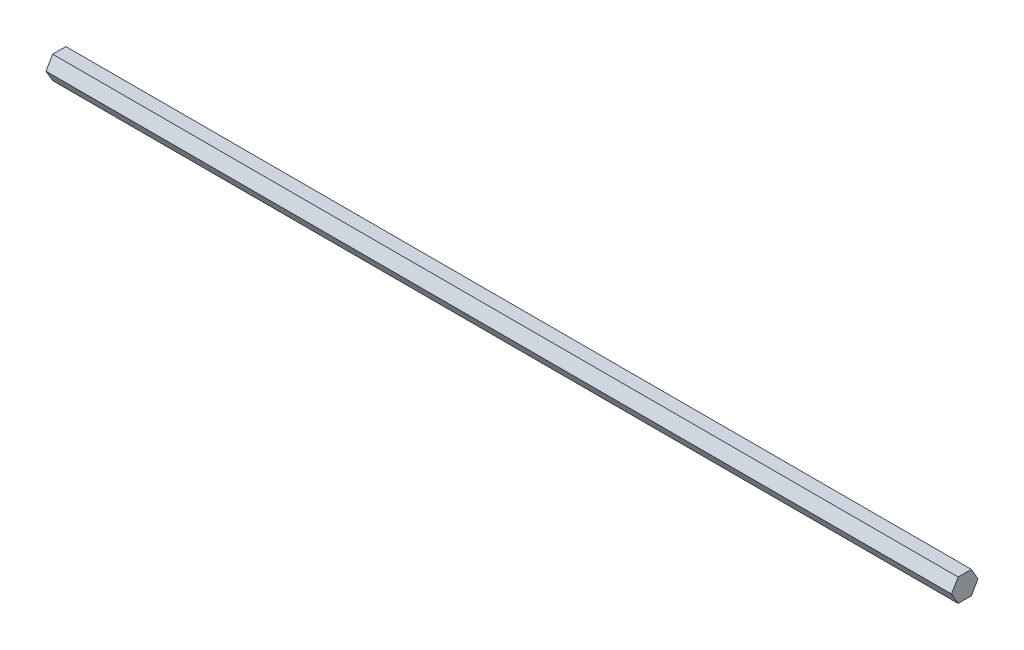
SolidWorks part; units mm, degrees
material "7075-T6 (SN)"
ref_plane "Front Plane" through (0, 0, 0) normal (0, 0, 1) x (1, 0, 0)
ref_plane "Top Plane" through (0, 0, 0) normal (0, 1, 0) x (1, 0, 0)
ref_plane "Right Plane" through (0, 0, 0) normal (1, 0, 0) x (0, 0, -1)
sketch "Sketch1" plane through (0, 0, 0) normal (1, 0, 0) x (0, 0, -1)
  line L1 (-3.6662, 6.35) -> (-7.3323, 0)
  line L2 (-7.3323, 0) -> (-3.6662, -6.35)
  line L3 (-3.6662, -6.35) -> (3.6662, -6.35)
  line L4 (3.6662, -6.35) -> (7.3323, 0)
  line L5 (7.3323, 0) -> (3.6662, 6.35)
  line L6 (3.6662, 6.35) -> (-3.6662, 6.35)
  circle A0 centre (0, 0) radius 6.35 construction
  dimension "D1" = 12.7
extrude "Boss-Extrude1" add sketch "Sketch1" along normal mid plane 501.65
